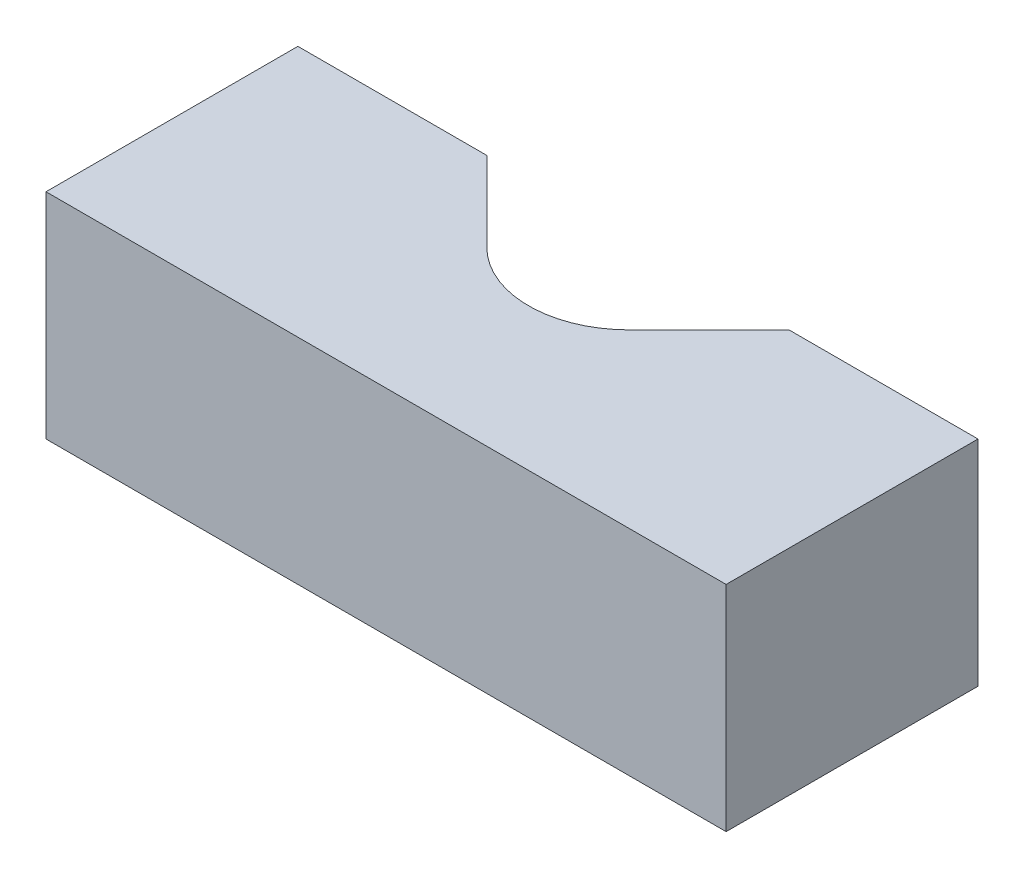
SolidWorks part; units mm, degrees
ref_plane "Front Plane" through (0, 0, 0) normal (0, 0, 1) x (1, 0, 0)
ref_plane "Top Plane" through (0, 0, 0) normal (0, 1, 0) x (1, 0, 0)
ref_plane "Right Plane" through (0, 0, 0) normal (1, 0, 0) x (0, 0, -1)
sketch "Sketch1" plane through (0, 0, 0) normal (0, 1, 0) x (1, 0, 0)
  line L1 (7.6179, -14.2219) -> (7.6179, -1.524) construction
  line L2 (7.6179, -1.524) -> (0, -9.1419)
  line L3 (0, 0) -> (0, -14.2219) construction
  line L5 (-7.6179, -1.524) -> (0, -9.1419)
  line L6 (7.6179, -1.524) -> (17.1429, -1.524)
  line L7 (17.1429, -1.524) -> (17.1429, -14.2219)
  line L8 (-21.5324, 0) -> (21.5324, 0) construction
  line L9 (-17.1429, -14.2219) -> (17.1429, -14.2219)
  line L10 (-7.6179, -14.2219) -> (-7.6179, -1.524) construction
  line L12 (-17.1429, -1.524) -> (-17.1429, -14.2219)
  line L13 (-7.6179, -1.524) -> (-17.1429, -1.524)
  circle A0 centre (0, 0) radius 6.4643 construction
  point P3 (0, 0)
  point P5 (0, 0)
  point P11 (0, 0)
  dimension "D1" = 12.9286
  dimension "D2" = 45
  dimension "D3" = 5.08
  dimension "D4" = 9.525
  dimension "D5" = 1.524
extrude "Boss-Extrude1" add sketch "Sketch1" along normal blind 10.795
fillet "Fillet1" radius 5.08 1 edges at (0, 5.3975, 9.1419)
